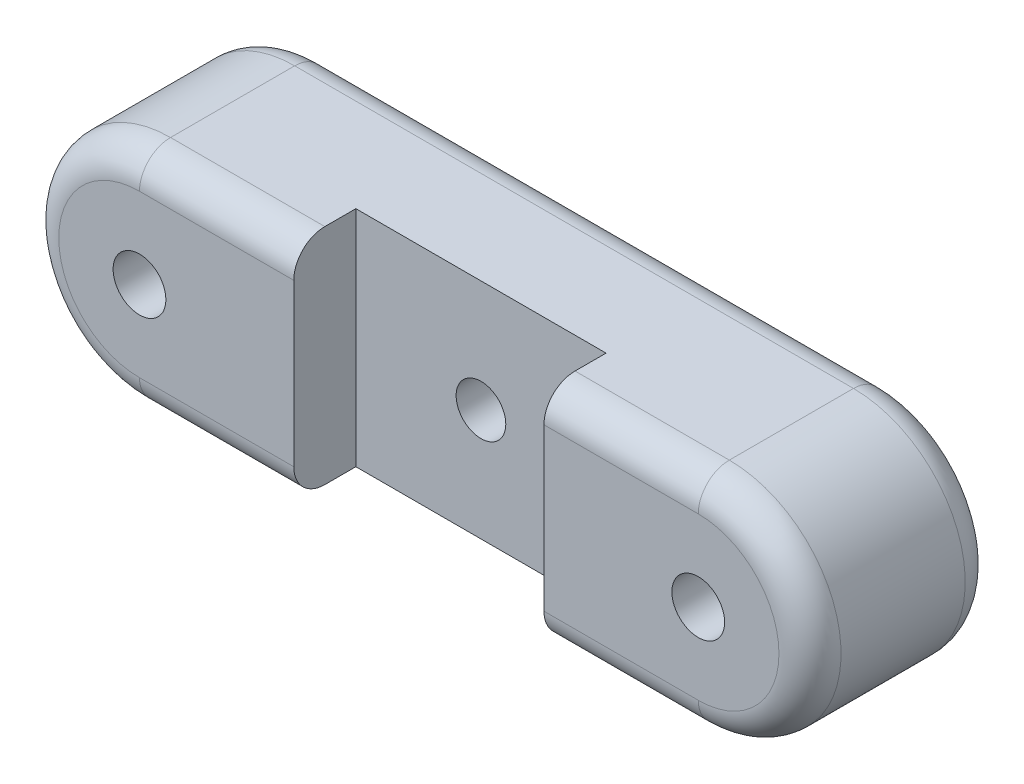
SolidWorks part; units mm, degrees
ref_plane "Front Plane" through (0, 0, 0) normal (0, 0, 1) x (1, 0, 0)
ref_plane "Top Plane" through (0, 0, 0) normal (0, 1, 0) x (1, 0, 0)
ref_plane "Right Plane" through (0, 0, 0) normal (1, 0, 0) x (0, 0, -1)
sketch "Sketch1" plane through (0, 0, 0) normal (0, 0, 1) x (1, 0, 0)
  line L0 (-45, 0) -> (45, 0) construction
  line L1 (-45, 18) -> (45, 18)
  line L2 (-45, -18) -> (45, -18)
  circle A0 centre (-45, 0) radius 8.1
  circle A1 centre (45, 0) radius 8.1
  arc A2 (-45, 18) -> (-45, -18) centre (-45, 0) ccw
  arc A3 (45, -18) -> (45, 18) centre (45, 0) ccw
  point P4 (0, 0)
  dimension "D1" = 16.2
  dimension "D2" = 16.2
  dimension "D3" = 45
  dimension "D4" = 45
  dimension "D5" = 36
extrude "Boss-Extrude1" add sketch "Sketch1" against normal blind 30 from offset 1220
sketch "Sketch3" plane through (0, 0, 1220) normal (0, 0, 1) x (1, 0, 0)
  circle A0 centre (45, 0) radius 4.25
  circle A1 centre (-45, 0) radius 4.25
  circle A2 centre (45, 0) radius 8.1 construction
  circle A3 centre (-45, 0) radius 8.1 construction
  circle A4 centre (45, 0) radius 8.1
  circle A5 centre (-45, 0) radius 8.1
  dimension "D1" = 8.5
  dimension "D2" = 8.5
extrude "Boss-Extrude2" add sketch "Sketch3" against normal blind 10
sketch "Sketch4" plane through (0, 0, 1220) normal (0, 0, 1) x (1, 0, 0)
  line L0 (45, 18) -> (-45, 18) construction
  line L1 (-20.15, 18) -> (20.15, 18)
  line L2 (-20.15, 18) -> (-20.15, -18)
  line L3 (-20.15, -18) -> (20.15, -18)
  line L4 (20.15, 18) -> (20.15, -18)
  line L5 (-45, -18) -> (45, -18) construction
  dimension "D1" = 20.15
  dimension "D2" = 20.15
extrude "Cut-Extrude1" cut sketch "Sketch4" against normal blind 10
fillet "Fillet1" radius 5 4 edges at (63, 0, 1190) (0, -18, 1190) (-63, 0, 1190) (0, 18, 1190)
fillet "Fillet2" radius 5 6 edges at (32.575, 18, 1220) (63, 0, 1220) (-32.575, -18, 1220) (-63, 0, 1220) (32.575, -18, 1220) (-32.575, 18, 1220)
sketch "Sketch5" plane through (0, 0, 1210) normal (0, 0, 1) x (1, 0, 0)
  circle A0 centre (0, 0) radius 4
  dimension "D1" = 8
extrude "Cut-Extrude2" cut sketch "Sketch5" against normal blind 50
